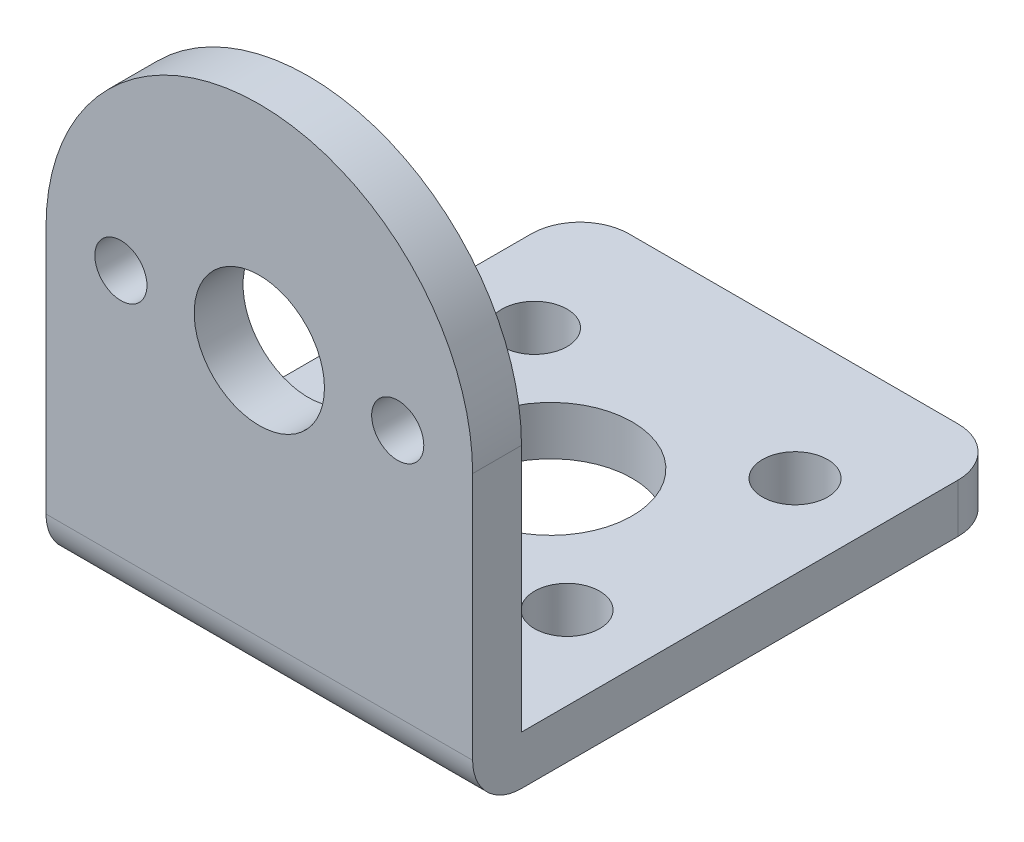
SolidWorks part; units mm, degrees
ref_plane "Front Plane" through (0, 0, 0) normal (0, 0, 1) x (1, 0, 0)
ref_plane "Top Plane" through (0, 0, 0) normal (0, 1, 0) x (1, 0, 0)
ref_plane "Right Plane" through (0, 0, 0) normal (1, 0, 0) x (0, 0, -1)
sketch "Sketch1" plane through (0, 0, 0) normal (0, 0, 1) x (1, 0, 0)
  line L0 (-13.1, 0) -> (-13.1, -18.25)
  line L5 (-13.1, 15.25) -> (13.1, 15.25) construction
  line L6 (-13.1, 15.25) -> (-13.1, -15.25) construction
  line L7 (-13.1, -15.25) -> (13.1, -15.25) construction
  line L8 (13.1, 15.25) -> (13.1, -15.25) construction
  line L9 (-13.1, -15.25) -> (13.1, -15.25) construction
  line L10 (-13.1, -15.25) -> (-13.1, -18.25) construction
  line L11 (-13.1, -18.25) -> (13.1, -18.25) construction
  line L12 (13.1, -15.25) -> (13.1, -18.25) construction
  line L13 (-13.1, -18.25) -> (13.1, -18.25)
  line L14 (13.1, -18.25) -> (13.1, 0)
  arc A0 (-13.1, 0) -> (13.1, 0) centre (0, 0) cw
  point P4 (0, 15.25)
  point P6 (-13.1, 0)
  circle B0 centre (0, 0) radius 4
  circle B1 centre (-8.5, 0) radius 1.6
  circle B2 centre (8.5, 0) radius 1.6
  dimension "D1" = 26.2
  dimension "D2" = 30.5
  dimension "D3" = 3
sketch_block_instance "Block-JGA25-371-2"
sketch_block "Block-JGA25-371" parameters "D1"=8, "D3"=3.2, "D4"=25, "D2"=17
extrude "JGA25-Screws" add sketch "Sketch1" along normal blind 3
sketch "Sketch2" plane through (0, -18.25, 0) normal (0, -1, 0) x (1, 0, 0)
  line L1 (-13.1, 0) -> (13.1, 0)
  line L2 (-13.1, 0) -> (-13.1, -29.8)
  line L3 (-13.1, -29.8) -> (13.1, -29.8)
  line L4 (13.1, 0) -> (13.1, -29.8)
  line B0 (13.1, -29.8) -> (-13.1, -29.8) construction
  circle B1 centre (0, -14.9) radius 5
  circle B2 centre (8, -21.9) radius 2
  circle B3 centre (-8, -21.9) radius 2
  circle B4 centre (8, -7.9) radius 2
  circle B5 centre (-8, -7.9) radius 2
  dimension "D1" = 29.8
sketch_block_instance "Block-JGA25-371-Bracket-1"
sketch_block "Block1" parameters "D1"=4, "D4"=10, "D2"=16, "D3"=14, "D5"=29.8, "D6"=3, "D7"=26.2
extrude "Bracket-Screws" add sketch "Sketch2" against normal blind 3
fillet "L-Shape-Fillet" radius 3 1 edges at (0, -18.25, 3)
fillet "Corner-Fillets" radius 3 2 edges at (13.1, -16.75, -29.8) (-13.1, -16.75, -29.8)
